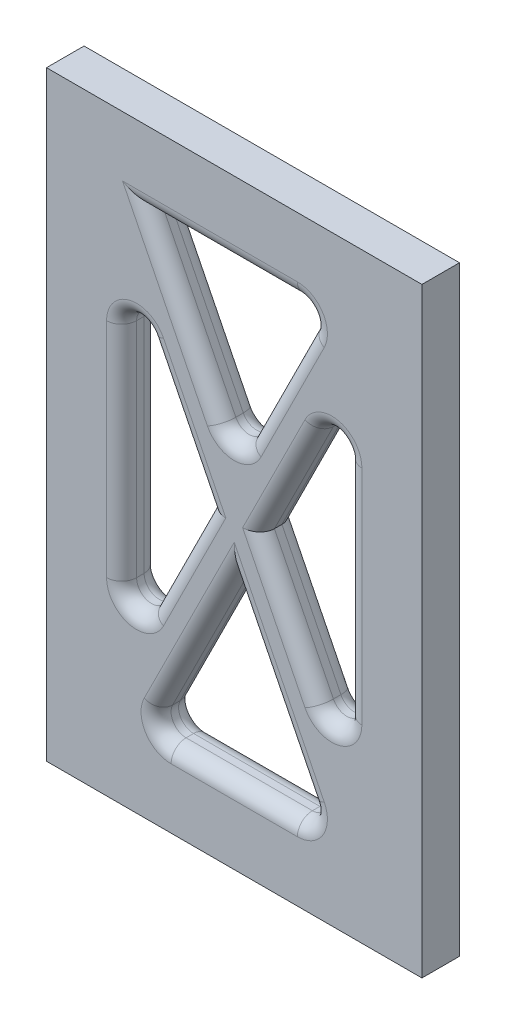
SolidWorks part; units mm, degrees
ref_plane "Front Plane" through (0, 0, 0) normal (0, 0, 1) x (1, 0, 0)
ref_plane "Top Plane" through (0, 0, 0) normal (0, 1, 0) x (1, 0, 0)
ref_plane "Right Plane" through (0, 0, 0) normal (1, 0, 0) x (0, 0, -1)
sketch "Sketch1" plane through (0, 0, 0) normal (0, 0, 1) x (1, 0, 0)
  line L0 (10, 16.7082) -> (10, 63.2918)
  line L1 (0, 0) -> (50, 0)
  line L2 (0, 0) -> (0, 80)
  line L3 (0, 80) -> (50, 80)
  line L4 (50, 0) -> (50, 80)
  line L5 (13.3541, 70) -> (36.6459, 70)
  line L6 (40, 16.7082) -> (40, 63.2918)
  line L7 (13.3541, 10) -> (36.6459, 10)
  line L10 (10, 63.2918) -> (21.6459, 40)
  line L11 (13.3541, 10) -> (25, 33.2918)
  line L12 (13.3541, 70) -> (25, 46.7082)
  line L13 (10, 16.7082) -> (21.6459, 40)
  line L18 (25, 33.2918) -> (36.6459, 10)
  line L19 (25, 46.7082) -> (36.6459, 70)
  line L20 (28.3541, 40) -> (40, 16.7082)
  line L21 (28.3541, 40) -> (40, 63.2918)
  line L22 (10, 10) -> (10, 70) construction
  line L24 (10, 70) -> (40, 70) construction
  line L26 (40, 10) -> (40, 70) construction
  line L27 (10, 10) -> (40, 10) construction
  dimension "D1" = 80
  dimension "D2" = 50
  dimension "D3" = 10
extrude "Boss-Extrude1" add sketch "Sketch1" along normal blind 5
fillet "Fillet1" radius 2 32 edges at (40, 40, 5) (34.1771, 51.6459, 5) (34.1771, 28.3541, 5) (30.8229, 58.3541, 5) (25, 70, 5) (19.1771, 58.3541, 5) (10, 40, 5) (15.8229, 28.3541, 5) (15.8229, 51.6459, 5) (25, 10, 5) (30.8229, 21.6459, 5) (19.1771, 21.6459, 5) (30.8229, 21.6459, 0) (19.1771, 21.6459, 0) (34.1771, 51.6459, 0) (34.1771, 28.3541, 0) (25, 70, 0) (19.1771, 58.3541, 0) (15.8229, 28.3541, 0) (15.8229, 51.6459, 0) (36.6459, 10, 2.5) (13.3541, 10, 2.5) (25, 10, 0) (40, 63.2918, 2.5) (40, 16.7082, 2.5) (40, 40, 0) (36.6459, 70, 2.5) (25, 46.7082, 2.5) (30.8229, 58.3541, 0) (10, 16.7082, 2.5) (10, 63.2918, 2.5) (10, 40, 0)
